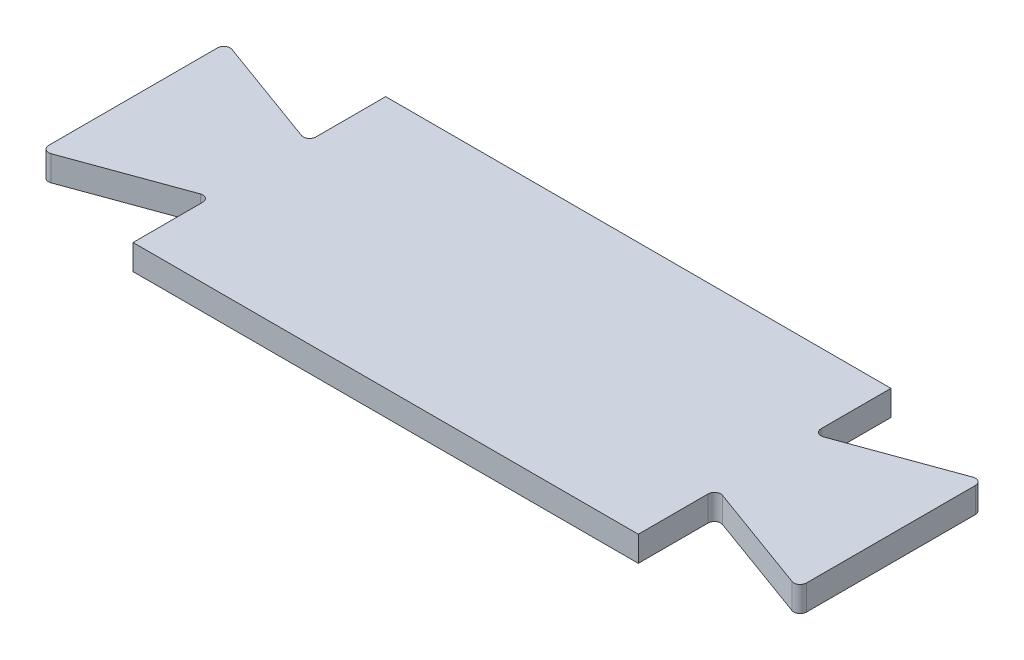
SolidWorks part; units mm, degrees
ref_plane "Front Plane" through (0, 0, 0) normal (0, 0, 1) x (1, 0, 0)
ref_plane "Top Plane" through (0, 0, 0) normal (0, 1, 0) x (1, 0, 0)
ref_plane "Right Plane" through (0, 0, 0) normal (1, 0, 0) x (0, 0, -1)
sketch "Sketch1" plane through (0, 0, 0) normal (0, 1, 0) x (1, 0, 0)
  line L0 (-10, 1.8801) -> (-15, 3.7)
  line L1 (-10, -5) -> (10, -5)
  line L2 (-10, -5) -> (-10, -1.8801)
  line L3 (-10, 5) -> (10, 5)
  line L4 (10, -5) -> (10, -1.8801)
  line L5 (-10, -5) -> (10, 5) construction
  line L6 (-10, 5) -> (10, -5) construction
  line L7 (-15, 3.7) -> (-15, -3.7)
  line L8 (-10, 0) -> (-18.3718, 0) construction
  line L9 (-10, -1.8801) -> (-15, -3.7)
  line L10 (-10, 1.8801) -> (-10, 5)
  line L11 (0, 0) -> (0, 5) construction
  line L12 (10, -1.8801) -> (15, -3.7)
  line L13 (15, 3.7) -> (15, -3.7)
  line L14 (10, 1.8801) -> (15, 3.7)
  line L15 (10, 1.8801) -> (10, 5)
  point P0 (0, 0)
  point P13 (-15, 0)
  dimension "D1" = 10
  dimension "D2" = 20
  dimension "D3" = 3.7
  dimension "D4" = 70
  dimension "D5" = 5
extrude "Boss-Extrude1" add sketch "Sketch1" along normal blind 1
fillet "Fillet1" radius 0.25 8 edges at (-10, 0.5, 1.8801) (-15, 0.5, 3.7) (-15, 0.5, -3.7) (-10, 0.5, -1.8801) (10, 0.5, -1.8801) (15, 0.5, -3.7) (15, 0.5, 3.7) (10, 0.5, 1.8801)
